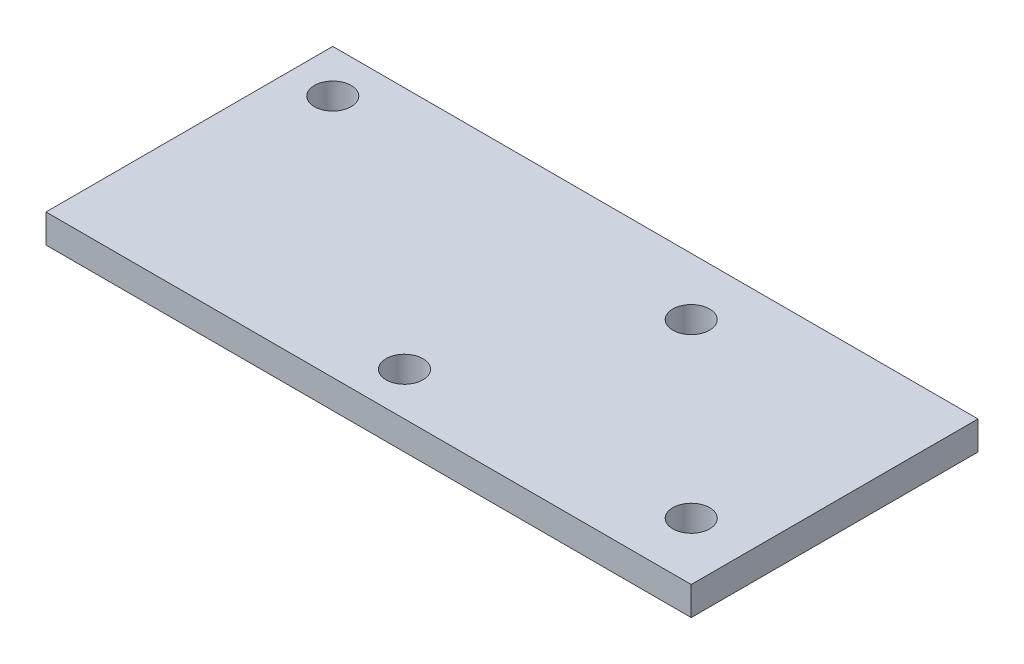
SolidWorks part; units mm, degrees
ref_plane "Front Plane" through (0, 0, 0) normal (0, 0, 1) x (1, 0, 0)
ref_plane "Top Plane" through (0, 0, 0) normal (0, 1, 0) x (1, 0, 0)
ref_plane "Right Plane" through (0, 0, 0) normal (1, 0, 0) x (0, 0, -1)
sketch "Sketch1" plane through (0, 0, 0) normal (0, 1, 0) x (1, 0, 0)
  line L1 (-28.575, 12.7) -> (28.575, 12.7)
  line L2 (-28.575, 12.7) -> (-28.575, -12.7)
  line L3 (-28.575, -12.7) -> (28.575, -12.7)
  line L4 (28.575, 12.7) -> (28.575, -12.7)
  line L5 (-28.575, 12.7) -> (28.575, -12.7) construction
  line L6 (-28.575, -12.7) -> (28.575, 12.7) construction
  point P0 (0, 0)
  dimension "D1" = 25.4
  dimension "D2" = 57.15
extrude "Boss-Extrude1" add sketch "Sketch1" along normal blind 2.54
hole_wizard "#4 Clearance Hole1" positions "Sketch3" profile "Sketch2" hole size "#4" standard "ANSI Inch" end condition up to next
sketch "Sketch3" plane through (0, 2.54, 0) normal (0, 1, 0) x (1, 0, 0)
  line L1 (-28.575, -12.7) -> (28.575, -12.7) construction
  line L2 (-28.575, 12.7) -> (-28.575, -12.7) construction
  point P0 (-24.765, 8.89)
  point P2 (-0.635, -8.89)
  point P4 (8.255, 7.62)
  point P6 (23.495, -7.62)
  dimension "D1" = 21.59
  dimension "D2" = 3.81
  dimension "D3" = 3.81
  dimension "D4" = 27.94
  dimension "D5" = 36.83
  dimension "D6" = 20.32
  dimension "D7" = 52.07
  dimension "D8" = 5.08
sketch "Sketch2" plane through (-24.765, 2.54, -8.89) normal (1, 0, 0) x (0, 0, 1)
  line L0 (0, 0) -> (0, 2.54)
  line L1 (0, 2.54) -> (1.6319, 2.54)
  line L2 (1.6319, 2.54) -> (1.6319, 0)
  line L5 (1.6319, 0) -> (0, 0)
  line L11 (0, -6.35) -> (0, 107.95) construction
  dimension "Thru Hole Dia." = 3.2639
  dimension "Thru Hole Depth" = 2.54
